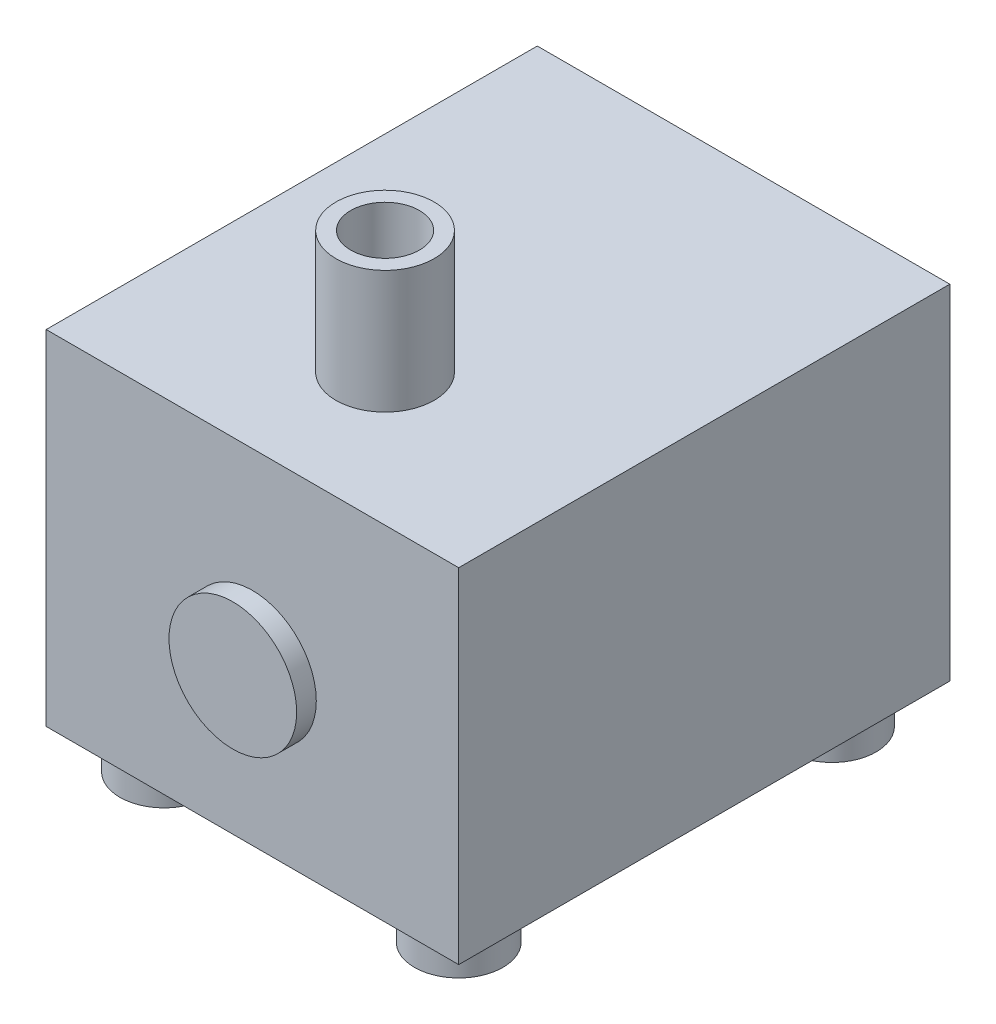
SolidWorks part; units mm, degrees
other "ABS_housing_PHYSICAL_MATERIAL_UNVERIFIED"
ref_plane "Front Plane" through (0, 0, 0) normal (0, 0, 1) x (1, 0, 0)
ref_plane "Top Plane" through (0, 0, 0) normal (0, 1, 0) x (1, 0, 0)
ref_plane "Right Plane" through (0, 0, 0) normal (1, 0, 0) x (0, 0, -1)
sketch "Sketch1" plane through (0, 0, 0) normal (0, 1, 0) x (1, 0, 0)
  line L1 (-42, -50) -> (42, -50)
  line L2 (-42, -50) -> (-42, 50)
  line L3 (-42, 50) -> (42, 50)
  line L4 (42, -50) -> (42, 50)
extrude "Listing_envelope_100x84x78" add sketch "Sketch1" along normal blind 70 from offset 8 separate body
sketch "Sketch2" plane through (0, 0, 0) normal (0, 1, 0) x (1, 0, 0)
  circle A0 centre (-30, -38) radius 9
extrude "Suction_foot_ASSUMED" add sketch "Sketch2" along normal blind 8 from offset 0 separate body
sketch "Sketch3" plane through (0, 0, 0) normal (0, 1, 0) x (1, 0, 0)
  circle A0 centre (-30, 38) radius 9
extrude "Boss-Extrude3" add sketch "Sketch3" along normal blind 8 from offset 0 separate body
sketch "Sketch4" plane through (0, 0, 0) normal (0, 1, 0) x (1, 0, 0)
  circle A0 centre (30, -38) radius 9
extrude "Boss-Extrude4" add sketch "Sketch4" along normal blind 8 from offset 0 separate body
sketch "Sketch5" plane through (0, 0, 0) normal (0, 1, 0) x (1, 0, 0)
  circle A0 centre (30, 38) radius 9
extrude "Boss-Extrude5" add sketch "Sketch5" along normal blind 8 from offset 0 separate body
sketch "Sketch6" plane through (0, 0, 0) normal (0, 1, 0) x (1, 0, 0)
  circle A0 centre (0, -23) radius 10
  circle A1 centre (0, -23) radius 7
extrude "Nozzle_extra_clearance_ASSUMED" add sketch "Sketch6" along normal blind 25 from offset 78 separate body
sketch "Sketch7" plane through (0, 0, 0) normal (0, 0, 1) x (1, 0, 0)
  circle A0 centre (0, 40) radius 13
extrude "Flow_adjustment_knob_ASSUMED" add sketch "Sketch7" along normal blind 4 from offset 50 separate body
